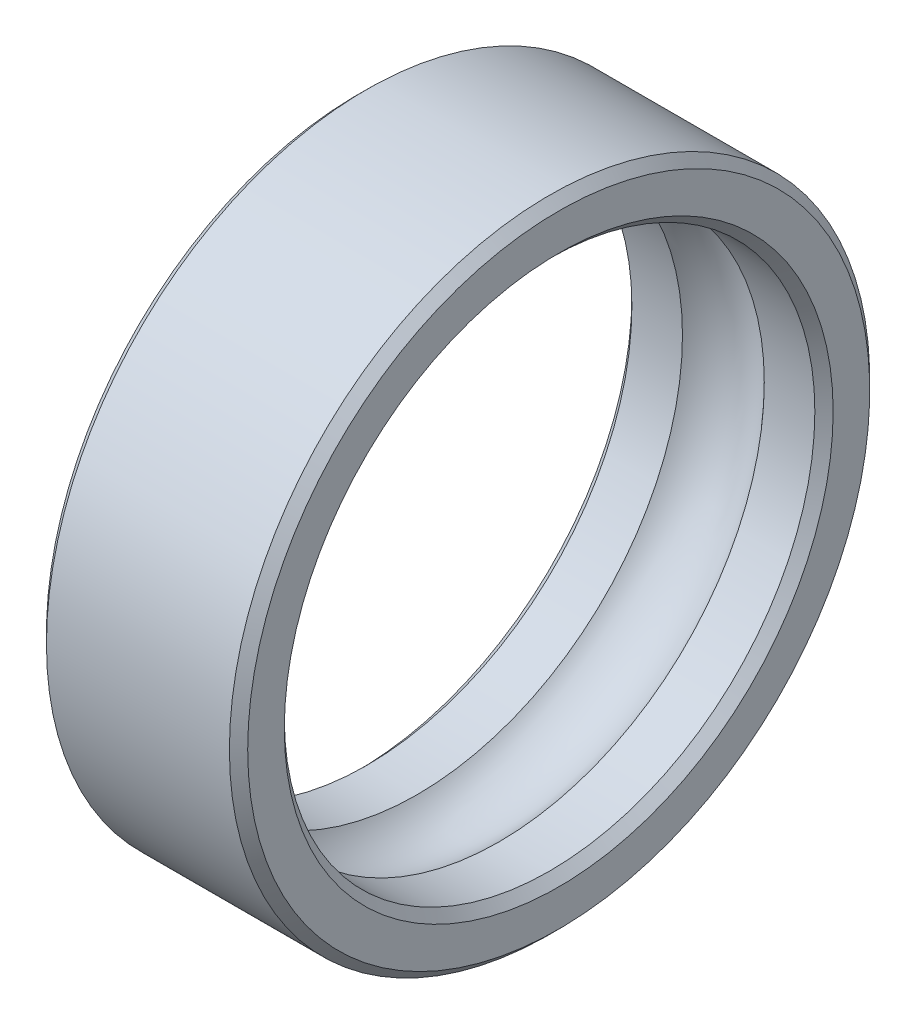
SolidWorks part; units mm, degrees
other "Camera1"
ref_plane "Front Plane" through (0, 0, 0) normal (0, 0, 1) x (1, 0, 0)
ref_plane "Top Plane" through (0, 0, 0) normal (0, 1, 0) x (1, 0, 0)
ref_plane "Right Plane" through (0, 0, 0) normal (1, 0, 0) x (0, 0, -1)
sketch "Sketch1" plane through (0, 0, 0) normal (0, 0, 1) x (1, 0, 0)
  line L0 (-7.5, 0) -> (12.1123, 0) construction
  line L1 (0, 7.5) -> (0, 0) construction
  line L2 (5.5, 14.5) -> (2.2361, 14.5)
  line L3 (5.5, 14.5) -> (5.5, 17.5)
  line L4 (5.5, 17.5) -> (-5.5, 17.5)
  line L5 (-5.5, 14.5) -> (-5.5, 17.5)
  line L6 (5.5, 14.5) -> (-5.5, 17.5) construction
  line L7 (5.5, 17.5) -> (-5.5, 14.5) construction
  line L8 (-2.2361, 14.5) -> (-5.5, 14.5)
  arc A0 (-2.2361, 14.5) -> (2.2361, 14.5) centre (0, 12.5) cw
  point P3 (0, 16)
  point P13 (0, 15.5)
  dimension "D4" = 2
  dimension "D5" = 3
  dimension "D1" = 11
  dimension "D2" = 14.5
  dimension "D3" = 17.5
  dimension "D6" = 7.5
  dimension "D7" = 3
  dimension "D8" = 12.5
  dimension "D9" = 1
revolve "Revolve1" add sketch "Sketch1" angle 360 about L0
chamfer "Chamfer1" distance 0.5 angle 45 2 edges at (5.5, 0, 17.5) (-5.5, 0, 17.5)
chamfer "Chamfer2" distance 0.5 angle 45 2 edges at (5.5, 0, 14.5) (-5.5, 0, 14.5)
